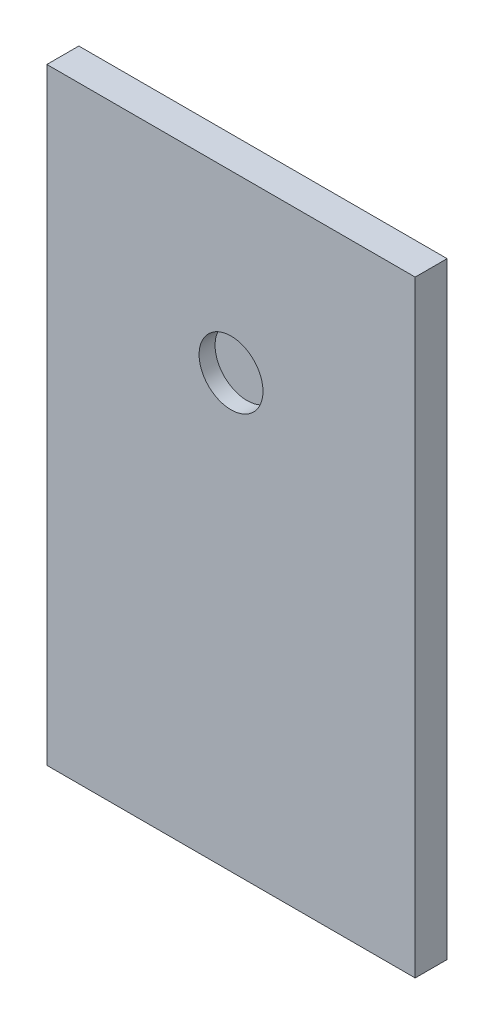
SolidWorks part; units mm, degrees
ref_plane "정면" through (0, 0, 0) normal (0, 0, 1) x (1, 0, 0)
ref_plane "윗면" through (0, 0, 0) normal (0, 1, 0) x (1, 0, 0)
ref_plane "우측면" through (0, 0, 0) normal (1, 0, 0) x (0, 0, -1)
sketch "스케치1" plane through (0, 0, 0) normal (0, 0, 1) x (1, 0, 0)
  line L1 (-28.82, 62.5) -> (28.82, 62.5)
  line L2 (-28.82, 62.5) -> (-28.82, -62.5)
  line L3 (-28.82, -62.5) -> (28.82, -62.5)
  line L4 (28.82, 62.5) -> (28.82, -62.5)
  line L5 (-28.82, 62.5) -> (28.82, -62.5) construction
  line L6 (-28.82, -62.5) -> (28.82, 62.5) construction
  point P0 (0, 0)
  dimension "D1" = 57.64
  dimension "D2" = 125
extrude "보스-돌출1" add sketch "스케치1" along normal blind 5
sketch "스케치2" plane through (0, 0, 5) normal (0, 0, 1) x (1, 0, 0)
  arc A19 (5, 5.1017) -> (-5, 5.1017) centre (0, 5.1017) cw
  arc A20 (-5, 5.1017) -> (5, 5.1017) centre (0, 5.1017) cw
  dimension "D1" = 5
extrude "컷-돌출1" cut sketch "스케치2" against normal blind 2.5 contours A20 A19
sketch "스케치3" plane through (0, 0, 5) normal (0, 0, 1) x (1, 0, 0)
  line L1 (-28.82, 62.5) -> (28.82, 62.5)
  line L2 (-28.82, 62.5) -> (-28.82, 32.5)
  line L3 (-28.82, 32.5) -> (28.82, 32.5)
  line L4 (28.82, 62.5) -> (28.82, 32.5)
  dimension "D1" = 30
extrude "컷-돌출2" cut sketch "스케치3" against normal blind 10
